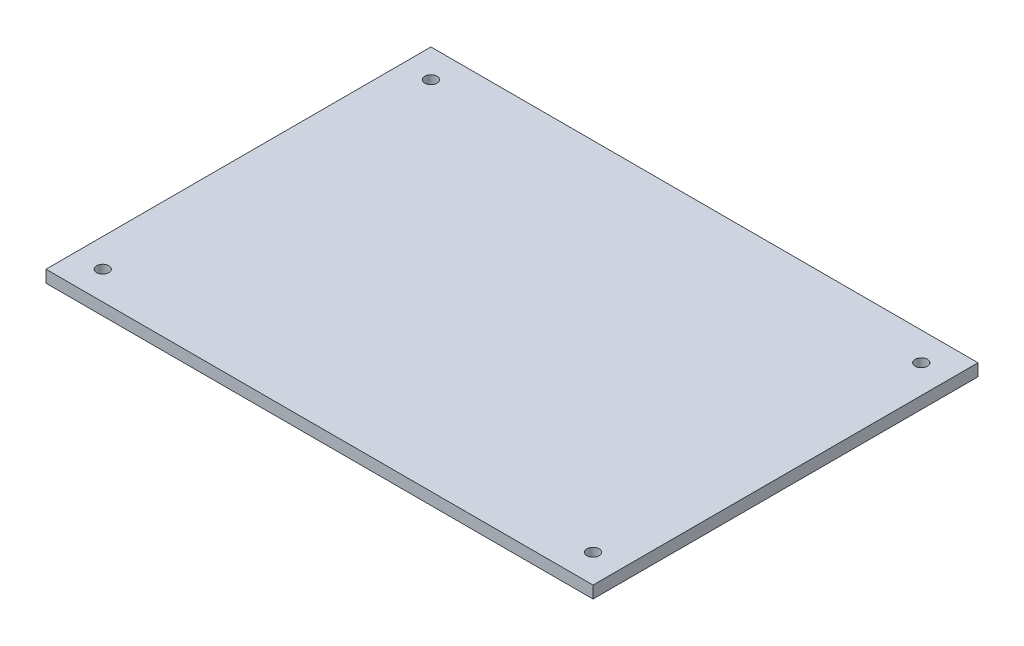
SolidWorks part; units mm, degrees
ref_plane "Front Plane" through (0, 0, 0) normal (0, 0, 1) x (1, 0, 0)
ref_plane "Top Plane" through (0, 0, 0) normal (0, 1, 0) x (1, 0, 0)
ref_plane "Right Plane" through (0, 0, 0) normal (1, 0, 0) x (0, 0, -1)
sketch "Sketch1" plane through (0, 0, 0) normal (0, 1, 0) x (1, 0, 0)
  line L1 (67.5, -47.5) -> (-67.5, -47.5)
  line L2 (67.5, -47.5) -> (67.5, 47.5)
  line L3 (67.5, 47.5) -> (-67.5, 47.5)
  line L4 (-67.5, -47.5) -> (-67.5, 47.5)
  line L5 (67.5, -47.5) -> (-67.5, 47.5) construction
  line L6 (67.5, 47.5) -> (-67.5, -47.5) construction
  point P0 (0, 0)
  dimension "D1" = 95
  dimension "D2" = 135
extrude "Boss-Extrude1" add sketch "Sketch1" along normal blind 3
hole_wizard "#31 (0.12) Diameter Hole1" positions "Sketch3" profile "Sketch2" hole size "#31" standard "ANSI Inch" end condition through all
sketch "Sketch3" plane through (0, 3, 0) normal (0, 1, 0) x (1, 0, 0)
  line L0 (-67.5, 47.5) -> (-67.5, -47.5) construction
  line L1 (67.5, 47.5) -> (-67.5, 47.5) construction
  line L2 (67.5, -47.5) -> (67.5, 47.5) construction
  line L3 (-67.5, -47.5) -> (67.5, -47.5) construction
  point P0 (-60.5, 40.5)
  point P2 (-60.5, -40.5)
  point P4 (60.5, 40.5)
  point P6 (60.5, -40.5)
  dimension "D1" = 7
  dimension "D2" = 7
  dimension "D3" = 7
  dimension "D4" = 7
  dimension "D5" = 7
  dimension "D6" = 7
  dimension "D7" = 7
  dimension "D8" = 7
sketch "Sketch2" plane through (-60.5, 3, -40.5) normal (1, 0, 0) x (0, 0, 1)
  line L0 (0, 0) -> (0, 3)
  line L1 (0, 3) -> (1.5, 3)
  line L2 (1.5, 3) -> (1.5, 0)
  line L5 (1.5, 0) -> (0, 0)
  line L11 (0, -6.35) -> (0, 107.95) construction
  dimension "Thru Hole Dia." = 3
  dimension "Thru Hole Depth" = 3
